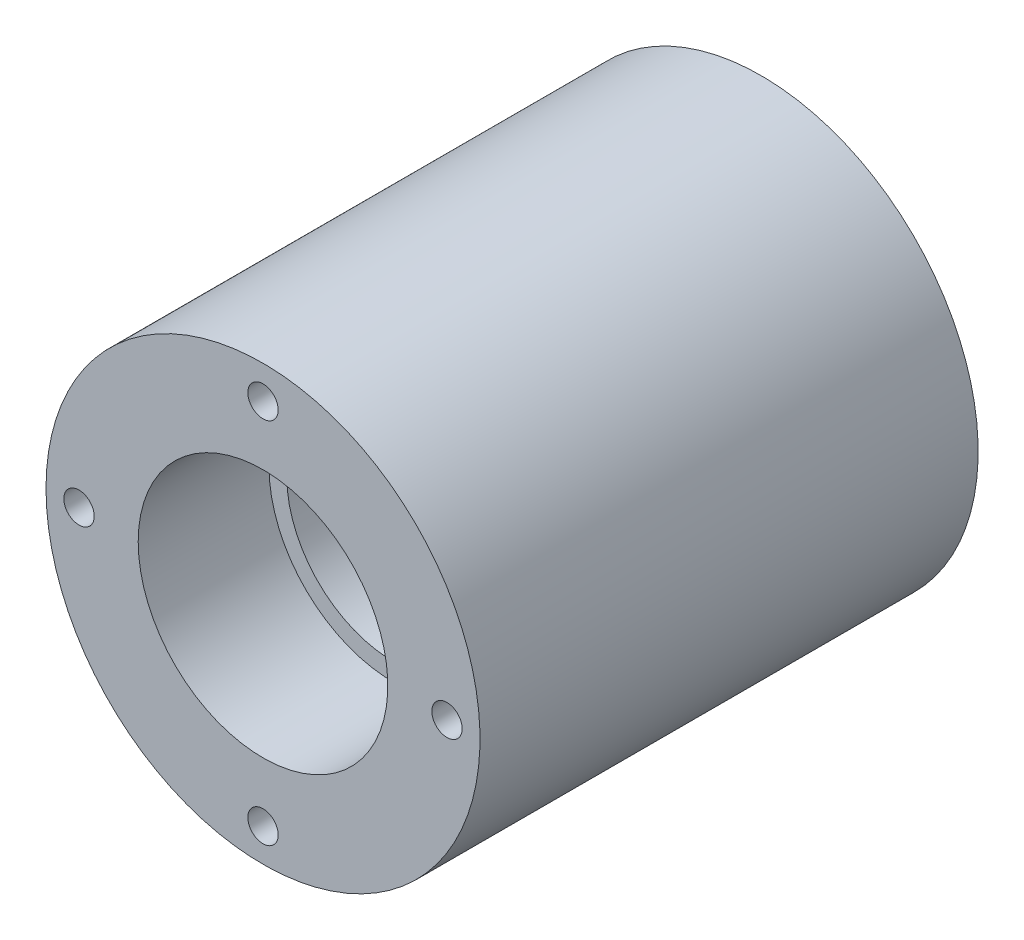
SolidWorks part; units mm, degrees
material "6061-T6 (SS)"
ref_plane "Front Plane" through (0, 0, 0) normal (0, 0, 1) x (1, 0, 0)
ref_plane "Top Plane" through (0, 0, 0) normal (0, 1, 0) x (1, 0, 0)
ref_plane "Right Plane" through (0, 0, 0) normal (1, 0, 0) x (0, 0, -1)
sketch "Shaft Sketch" plane through (0, 0, 0) normal (1, 0, 0) x (0, 0, -1)
  line L0 (141.5523, 0) -> (-87.5573, 0)
  line L1 (83.82, 36.5125) -> (0, 36.5125) construction
  line L2 (83.82, 36.5125) -> (83.82, -36.5125) construction
  line L3 (83.82, -36.5125) -> (0, -36.5125) construction
  line L4 (0, 36.5125) -> (0, -36.5125) construction
  line L5 (0, 36.5125) -> (-15.24, 36.5125) construction
  line L6 (0, 36.5125) -> (0, -36.5125) construction
  line L7 (0, -36.5125) -> (-15.24, -36.5125) construction
  line L8 (-15.24, 36.5125) -> (-15.24, -36.5125) construction
  line L9 (-25.4, 9.525) -> (0, 9.525)
  line L10 (-25.4, 9.525) -> (-25.4, -9.525)
  line L11 (-25.4, -9.525) -> (0, -9.525)
  line L12 (0, 9.525) -> (0, -9.525)
  line L13 (22, 10.0076) -> (10, 10.0076)
  line L14 (22, 10.0076) -> (22, -10.0076)
  line L15 (22, -10.0076) -> (10, -10.0076)
  line L16 (10, 10.0076) -> (10, -10.0076)
  line L17 (67.945, 9.9949) -> (55.945, 9.9949)
  line L18 (67.945, 9.9949) -> (67.945, -9.9949)
  line L19 (67.945, -9.9949) -> (55.945, -9.9949)
  line L20 (55.945, 9.9949) -> (55.945, -9.9949)
  line L22 (55.945, 9.9949) -> (22, 9.9949)
  line L23 (55.945, 9.9949) -> (55.945, -9.9949)
  line L24 (55.945, -9.9949) -> (22, -9.9949)
  line L25 (22, 9.9949) -> (22, -9.9949)
  line L26 (67.945, 9.525) -> (91.059, 9.525)
  line L27 (67.945, 9.525) -> (67.945, -9.525)
  line L28 (67.945, -9.525) -> (91.059, -9.525)
  line L29 (91.059, 9.525) -> (91.059, -9.525)
  line L30 (103.378, 7.9375) -> (100.838, 7.9375)
  line L31 (103.378, 7.9375) -> (103.378, -7.9375)
  line L32 (103.378, -7.9375) -> (100.838, -7.9375)
  line L33 (100.838, 7.9375) -> (100.838, -7.9375)
  line L34 (10, 12.5) -> (0, 12.5)
  line L35 (10, 12.5) -> (10, -12.5)
  line L36 (10, -12.5) -> (0, -12.5)
  line L37 (0, 12.5) -> (0, -12.5)
  line L38 (-44.4, 7.0002) -> (-29.4, 7.0002)
  line L39 (-44.4, 7.0002) -> (-44.4, -7.0002)
  line L40 (-44.4, -7.0002) -> (-29.4, -7.0002)
  line L41 (-29.4, 7.0002) -> (-29.4, -7.0002)
  line L42 (83.82, 36.5125) -> (93.345, 36.5125) construction
  line L43 (83.82, 36.5125) -> (83.82, -36.5125) construction
  line L44 (83.82, -36.5125) -> (93.345, -36.5125) construction
  line L45 (93.345, 36.5125) -> (93.345, -36.5125) construction
  line L46 (103.378, -7.9375) -> (91.059, -7.9375)
  line L47 (103.378, -7.9375) -> (103.378, 7.9375)
  line L48 (103.378, 7.9375) -> (91.059, 7.9375)
  line L49 (91.059, -7.9375) -> (91.059, 7.9375)
  line L54 (-25.4, 7.5) -> (-29.4, 7.5)
  line L55 (-25.4, 7.5) -> (-25.4, -7.5)
  line L56 (-25.4, -7.5) -> (-29.4, -7.5)
  line L57 (-29.4, 7.5) -> (-29.4, -7.5)
  line L58 (103.378, 3.8989) -> (131.445, 3.8989)
  line L59 (103.378, 3.8989) -> (103.378, -3.8989)
  line L60 (103.378, -3.8989) -> (131.445, -3.8989)
  line L61 (131.445, 3.8989) -> (131.445, -3.8989)
  point P66 (-22.86, -7.5)
sketch "Housing Sketch" plane through (0, 0, 0) normal (1, 0, 0) x (0, 0, -1)
  line L0 (67.945, 9.9949) -> (67.945, -9.9949) construction
  line L1 (55.945, 9.9949) -> (55.945, -9.9949) construction
  line L2 (22, 10.0076) -> (22, -10.0076) construction
  line L3 (10, 10.0076) -> (10, -10.0076) construction
  line L4 (0, 36.5125) -> (0, -36.5125) construction
  line L5 (83.82, 36.5125) -> (0, 36.5125) construction
  line L6 (83.82, 36.5125) -> (83.82, -36.5125) construction
  line L7 (67.945, 9.9949) -> (67.945, -9.9949)
  line L8 (55.945, 9.9949) -> (55.945, -9.9949)
  line L9 (22, 10.0076) -> (22, -10.0076)
  line L10 (10, 10.0076) -> (10, -10.0076)
  line L11 (0, 36.5125) -> (0, -36.5125)
  line L12 (83.82, 36.5125) -> (0, 36.5125)
  line L13 (83.82, 36.5125) -> (83.82, -36.5125)
  line L15 (-999.0031, 0) -> (48976.0676, 0)
  line L17 (83.82, 21) -> (55.945, 21)
  line L18 (55.945, 21) -> (55.945, 18)
  line L19 (55.945, 18) -> (22, 18)
  line L20 (22, 18) -> (22, 21)
  line L21 (22, 21) -> (0, 21)
  dimension "D1" = 21
  dimension "D2" = 3
revolve "Housing Revolve" add sketch "Housing Sketch" angle 360 about L0
ref_plane "Center Plane" through (0, 0, -41.91) normal (0, 0, -1) x (-1, 0, 0)
sketch "Bolt Location" plane through (0, 0, 0) normal (0, 0, 1) x (1, 0, 0)
  circle A0 centre (0, 0) radius 30.9575 construction
  point P3 (0, 30.9575)
  point P4 (30.9575, 0)
  point P5 (0, -30.9575)
  point P6 (-30.9575, 0)
  point P7 (-47.0885, 17.8863)
  dimension "D1" = 61.915
hole_wizard "Tap Drill for 1/4-20 Tap2" positions "Sketch6" profile "Sketch8" hole size "1/4-20" standard "ANSI Inch"
sketch "Sketch6" plane through (0, 0, 0) normal (0, 0, 1) x (1, 0, 0)
  point P0 (0, 30.9575)
  point P3 (30.9575, 0)
  point P6 (0, -30.9575)
  point P9 (-30.9575, 0)
sketch "Sketch8" plane through (0, 30.9575, 0) normal (1, 0, 0) x (0, -1, 0)
  line L0 (0, 0) -> (0, 14.2338)
  line L1 (0, 14.2338) -> (2.5527, 12.7)
  line L2 (2.5527, 12.7) -> (2.5527, 0)
  line L5 (2.5527, 0) -> (0, 0)
  line L10 (0, 14.2338) -> (-2.5527, 12.7) construction
  line L11 (0, -6.35) -> (0, 107.95) construction
  dimension "Hole Dia." = 5.1054
  dimension "Hole Depth" = 12.7
  dimension "Drill Angle" = 118
mirror "Mirror1" about plane through (0, 0, -41.91) normal (0, 0, -1) of "Tap Drill for 1/4-20 Tap2"
